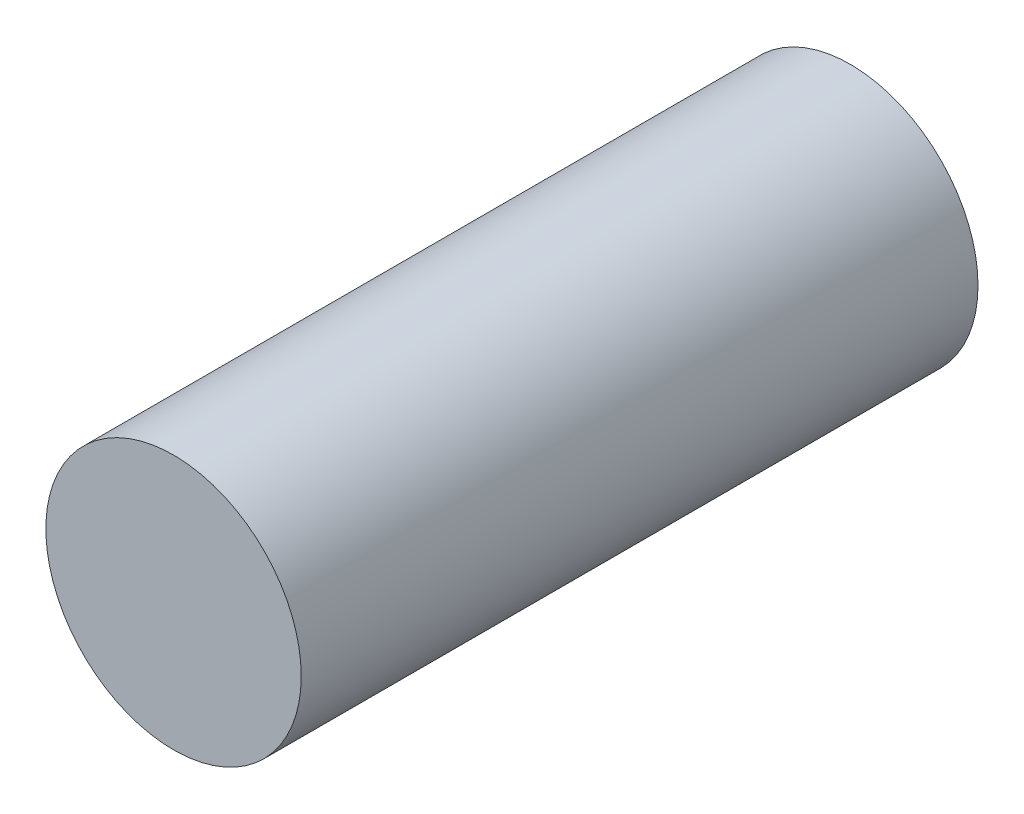
SolidWorks part; units mm, degrees
ref_plane "Front Plane" through (0, 0, 0) normal (0, 0, 1) x (1, 0, 0)
ref_plane "Top Plane" through (0, 0, 0) normal (0, 1, 0) x (1, 0, 0)
ref_plane "Right Plane" through (0, 0, 0) normal (1, 0, 0) x (0, 0, -1)
sketch "Sketch2" plane through (0, 0, 0) normal (0, 0, 1) x (1, 0, 0)
  circle A0 centre (0, 0) radius 50
  dimension "D1" = 100
extrude "Boss-Extrude1" add sketch "Sketch2" along normal blind 265
